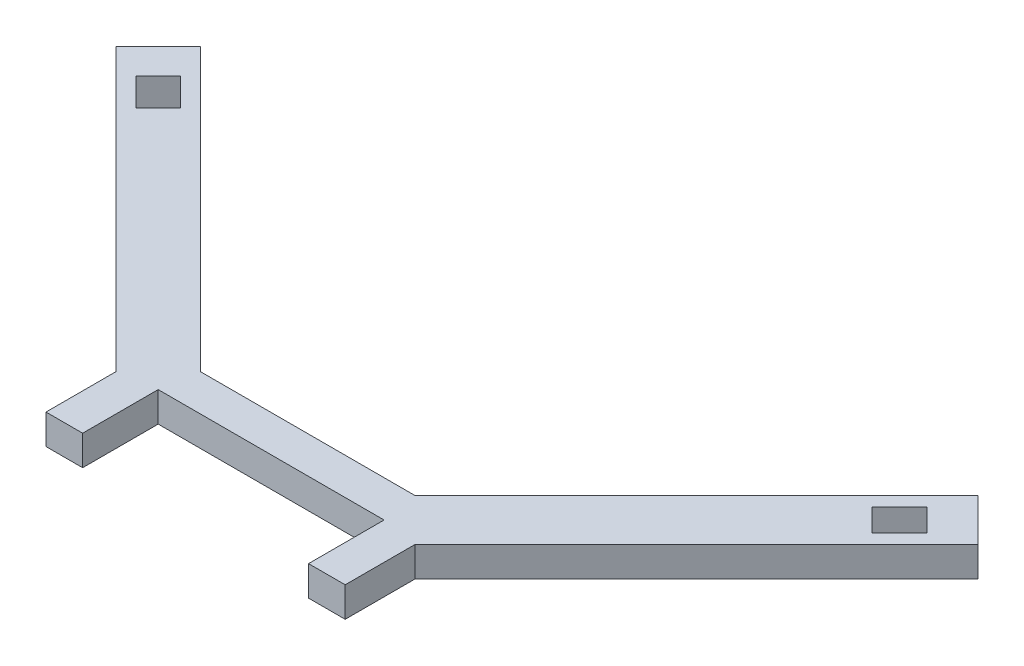
SolidWorks part; units mm, degrees
ref_plane "前视基准面" through (0, 0, 0) normal (0, 0, 1) x (1, 0, 0)
ref_plane "上视基准面" through (0, 0, 0) normal (0, 1, 0) x (1, 0, 0)
ref_plane "右视基准面" through (0, 0, 0) normal (1, 0, 0) x (0, 0, -1)
sketch "草图1" plane through (0, 0, 0) normal (0, 1, 0) x (1, 0, 0)
  line L0 (0, 0) -> (-212.132, 212.132)
  line L1 (0, 300) -> (0, 0)
  line L2 (0, 0) -> (212.132, 212.132)
  line L3 (0, 0) -> (127.2792, 127.2792)
  line L4 (127.2792, 127.2792) -> (0, 254.5584)
  line L5 (0, 254.5584) -> (-127.2792, 127.2792)
  line L6 (-127.2792, 127.2792) -> (0, 0)
  line L8 (-30, 30) -> (30, 30)
  line L9 (-30, 30) -> (-30, -30)
  line L10 (-30, -30) -> (30, -30)
  line L11 (30, 30) -> (30, -30)
  line L12 (-30, 30) -> (30, -30) construction
  line L13 (-30, -30) -> (30, 30) construction
  circle A0 centre (0, 0) radius 300
  dimension "D1" = 600
  dimension "D2" = 45
  dimension "D3" = 45
  dimension "D4" = 180
  dimension "D5" = 60
  dimension "D6" = 60
sketch "草图2" plane through (0, 0, 0) normal (0, 1, 0) x (1, 0, 0)
  line L0 (-40, 40) -> (-40, 10)
  line L1 (0, 0) -> (-212.132, 212.132) construction
  line L2 (-40, 10) -> (-30, 10)
  line L3 (-30, 30) -> (-30, -30) construction
  line L4 (-30, 10) -> (-30, 30)
  line L5 (-30, 30) -> (30, 30)
  line L6 (30, 30) -> (30, 10)
  line L7 (30, 30) -> (30, -30) construction
  line L8 (30, 10) -> (40, 10)
  line L9 (40, 10) -> (40, 40)
  line L10 (0, 0) -> (212.132, 212.132) construction
  line L11 (40, 40) -> (-40, 40)
  line L12 (-28.6863, 40) -> (-103.9447, 115.2584)
  line L13 (-103.9447, 115.2584) -> (-115.2584, 103.9447)
  line L14 (-115.2584, 103.9447) -> (-40, 28.6863)
  line L16 (28.6863, 40) -> (103.9447, 115.2584)
  line L17 (103.9447, 115.2584) -> (115.2584, 103.9447)
  line L18 (115.2584, 103.9447) -> (40, 28.6863)
  dimension "D1" = 20
  dimension "D2" = 20
  dimension "D3" = 10
  dimension "D4" = 10
  dimension "D5" = 8
  dimension "D6" = 8
  dimension "D7" = 155
  dimension "D8" = 8
  dimension "D9" = 8
  dimension "D10" = 155
sketch "草图3" plane through (0, 0, 0) normal (0, 1, 0) x (1, 0, 0)
  line L0 (0, -30) -> (127.2792, 97.2792)
  line L1 (127.2792, 97.2792) -> (0, 224.5584)
  line L2 (0, 224.5584) -> (-127.2792, 97.2792)
  line L3 (-127.2792, 97.2792) -> (0, -30)
  line L4 (0, 0) -> (212.132, 212.132) construction
  line L5 (0, 254.5584) -> (-127.2792, 127.2792) construction
  line L6 (0, 0) -> (-212.132, 212.132) construction
  line L7 (127.2792, 127.2792) -> (0, 254.5584) construction
  dimension "D1" = 180
  dimension "D2" = 180
extrude "凸台-拉伸1" add sketch "草图2" along normal blind 8 contours L13 L14 L0 L11 L12 | L18 L17 L16 L11 L9 | L9 L11 L0 L2 L4 L5 L6 L8
sketch "草图5" plane through (0, 8, 0) normal (0, 1, 0) x (1, 0, 0)
  line L0 (-101.1163, 89.8026) -> (-89.8026, 101.1163)
  line L1 (-115.2584, 103.9447) -> (-40, 28.6863) construction
  line L2 (-28.6863, 40) -> (-103.9447, 115.2584) construction
  line L3 (-103.9447, 115.2584) -> (-115.2584, 103.9447) construction
  line L4 (89.8026, 101.1163) -> (101.1163, 89.8026)
  line L5 (28.6863, 40) -> (103.9447, 115.2584) construction
  line L6 (115.2584, 103.9447) -> (40, 28.6863) construction
  line L7 (103.9447, 115.2584) -> (115.2584, 103.9447) construction
  line L8 (-92.4896, 98.4293) -> (-98.4293, 92.4896)
  line L9 (-92.4896, 98.4293) -> (-99.8435, 105.7832)
  line L10 (-98.4293, 92.4896) -> (-105.7832, 99.8435)
  line L11 (-99.8435, 105.7832) -> (-105.7832, 99.8435)
  line L12 (92.4896, 98.4293) -> (98.4293, 92.4896)
  line L13 (92.4896, 98.4293) -> (99.8435, 105.7832)
  line L14 (98.4293, 92.4896) -> (105.7832, 99.8435)
  line L15 (99.8435, 105.7832) -> (105.7832, 99.8435)
  dimension "D1" = 20
  dimension "D2" = 20
  dimension "D3" = 10.4
  dimension "D4" = 8.4
  dimension "D5" = 3.8
  dimension "D6" = 10.4
  dimension "D7" = 8.4
  dimension "D8" = 3.8
extrude "切除-拉伸1" cut sketch "草图5" against normal through all contours L9 L11 L10 L0 | L12 L13 L15 L14
sketch "草图6" plane through (0, 8, 0) normal (0, 1, 0) x (1, 0, 0)
  line L0 (0, 0) -> (212.132, 212.132) construction
  line L1 (-30.2, -30.2) -> (30.2, -30.2)
  line L2 (-30.2, -30.2) -> (-30.2, 30.2)
  line L3 (-30.2, 30.2) -> (30.2, 30.2)
  line L4 (30.2, -30.2) -> (30.2, 30.2)
  line L5 (-30.2, -30.2) -> (30.2, 30.2) construction
  line L6 (-30.2, 30.2) -> (30.2, -30.2) construction
  line L7 (30, 30) -> (30, -30) construction
  point P0 (0, 0)
  dimension "D1" = 0.2
extrude "切除-拉伸2" cut sketch "草图6" against normal through all
